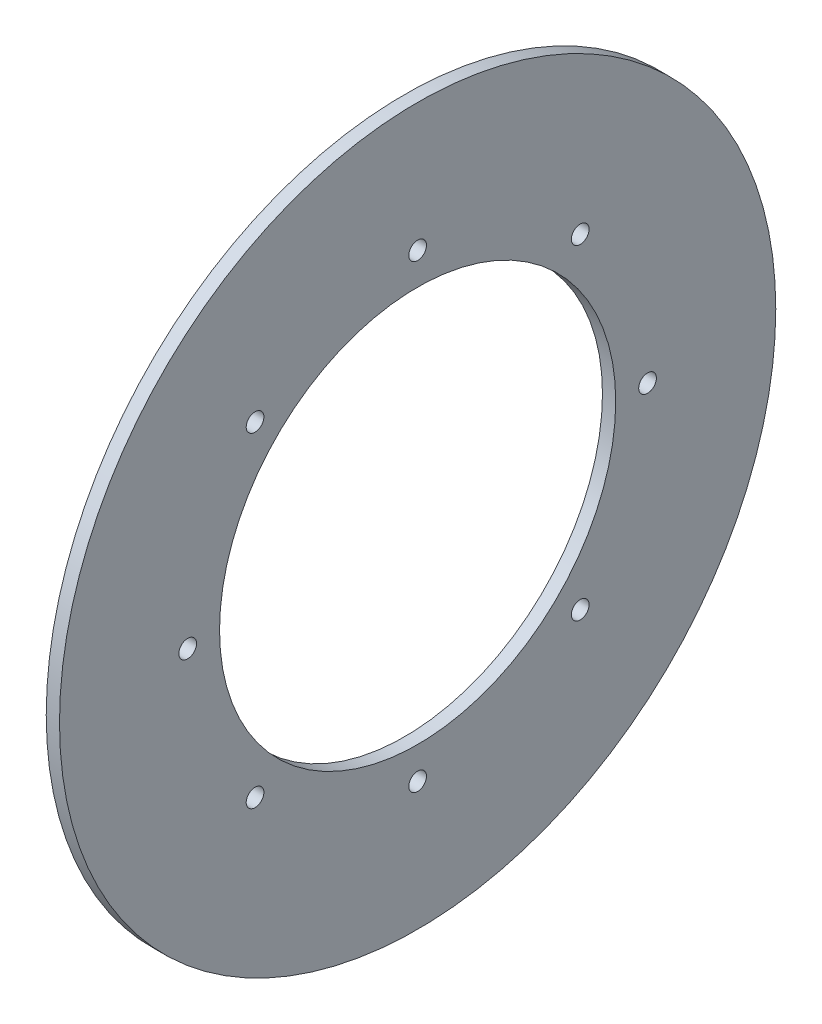
SolidWorks part; units mm, degrees
material "AISI 4340 Steel, normalized"
ref_plane "Front Plane" through (0, 0, 0) normal (0, 0, 1) x (1, 0, 0)
ref_plane "Top Plane" through (0, 0, 0) normal (0, 1, 0) x (1, 0, 0)
ref_plane "Right Plane" through (0, 0, 0) normal (1, 0, 0) x (0, 0, -1)
sketch "Sketch1" plane through (0, 0, 0) normal (1, 0, 0) x (0, 0, -1)
  circle A0 centre (0, 0) radius 82.5
  circle A1 centre (0, 0) radius 81
  circle A2 centre (0, 0) radius 44.8008
  circle A3 centre (0, 0) radius 43.8008
  dimension "D1" = 162
  dimension "D2" = 165
  dimension "D3" = 89.6016
  dimension "D4" = 87.6016
extrude "Boss-Extrude1" add sketch "Sketch1" along normal blind 3 contours A1 A2
sketch "Sketch2" plane through (3, 0, 0) normal (1, 0, 0) x (0, 0, -1)
  circle A0 centre (0, 52) radius 2
  dimension "D1" = 4
  dimension "D2" = 52
extrude "Cut-Extrude1" cut sketch "Sketch2" against normal blind 3
pattern_circular "CirPattern1" count 8 over 360 about axis through (0, 0, 0) along (1, 0, 0) of "Cut-Extrude1"
sketch "Sketch3" plane through (0, 0, 0) normal (1, 0, 0) x (0, 0, -1)
  line L1 (-15.4712, 69.6648) -> (0.0288, 69.6648)
  line L2 (-15.4712, 69.6648) -> (-15.4712, 59.4148)
  line L3 (-15.4712, 59.4148) -> (0.0288, 59.4148)
  line L4 (0.0288, 69.6648) -> (0.0288, 59.4148)
  line L5 (-15.4712, 69.6648) -> (0.0288, 59.4148) construction
  line L6 (-15.4712, 59.4148) -> (0.0288, 69.6648) construction
  point P0 (-7.7212, 64.5398)
  dimension "D1" = 64.5398
  dimension "D2" = 10.25
  dimension "D3" = 15.5
extrude "Boss-Extrude2" add sketch "Sketch3" against normal blind 1
sketch "Sketch4" plane through (0, 0, 0) normal (1, 0, 0) x (0, 0, -1)
  line L0 (0.0288, 59.4148) -> (0.0288, 69.6648) construction
  line L1 (-11.9712, 58.879) -> (0.0288, 58.879)
  line L2 (-11.9712, 58.879) -> (-11.9712, 59.879)
  line L3 (-11.9712, 59.879) -> (0.0288, 59.879)
  line L4 (0.0288, 58.879) -> (0.0288, 59.879)
  line L5 (-11.9712, 58.879) -> (0.0288, 59.879) construction
  line L6 (-11.9712, 59.879) -> (0.0288, 58.879) construction
  point P0 (-5.9712, 59.379)
  dimension "D1" = 1
  dimension "D2" = 12
extrude "Boss-Extrude3" add sketch "Sketch4" against normal blind 9
sketch "Sketch5" plane through (0, 59.879, 0) normal (0, 1, 0) x (1, 0, 0)
  line L1 (-4.5, -4.3982) -> (-8, -4.3982)
  line L2 (-4.5, -4.3982) -> (-4.5, -2.3982)
  line L3 (-4.5, -2.3982) -> (-8, -2.3982)
  line L4 (-8, -4.3982) -> (-8, -2.3982)
  line L6 (-1, -11.9712) -> (-1, 0.0288) construction
  dimension "D1" = 2
  dimension "D2" = 3.5
  dimension "D3" = 7
extrude "Boss-Extrude4" add sketch "Sketch5" along normal blind 9
pattern_circular "CirPattern5" count 3 over 360 about axis through (0, 0, 0) along (1, 0, 0) of "Boss-Extrude2", "Boss-Extrude4", "Boss-Extrude3"
